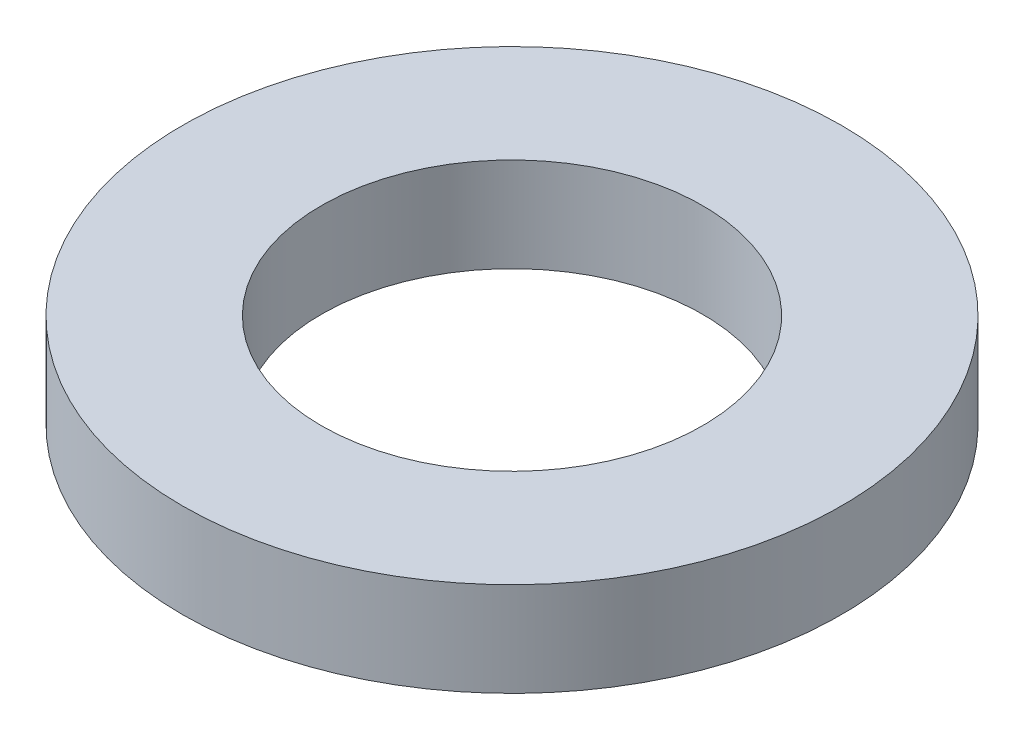
SolidWorks part; units mm, degrees
ref_plane "Front Plane" through (0, 0, 0) normal (0, 0, 1) x (1, 0, 0)
ref_plane "Top Plane" through (0, 0, 0) normal (0, 1, 0) x (1, 0, 0)
ref_plane "Right Plane" through (0, 0, 0) normal (1, 0, 0) x (0, 0, -1)
sketch "Sketch1" plane through (0, 0, 0) normal (0, 1, 0) x (1, 0, 0)
  circle A0 centre (0, 0) radius 4.05
  circle A1 centre (0, 0) radius 7
  dimension "D1" = 8.1
  dimension "D2" = 14
extrude "Boss-Extrude1" add sketch "Sketch1" along normal blind 2
